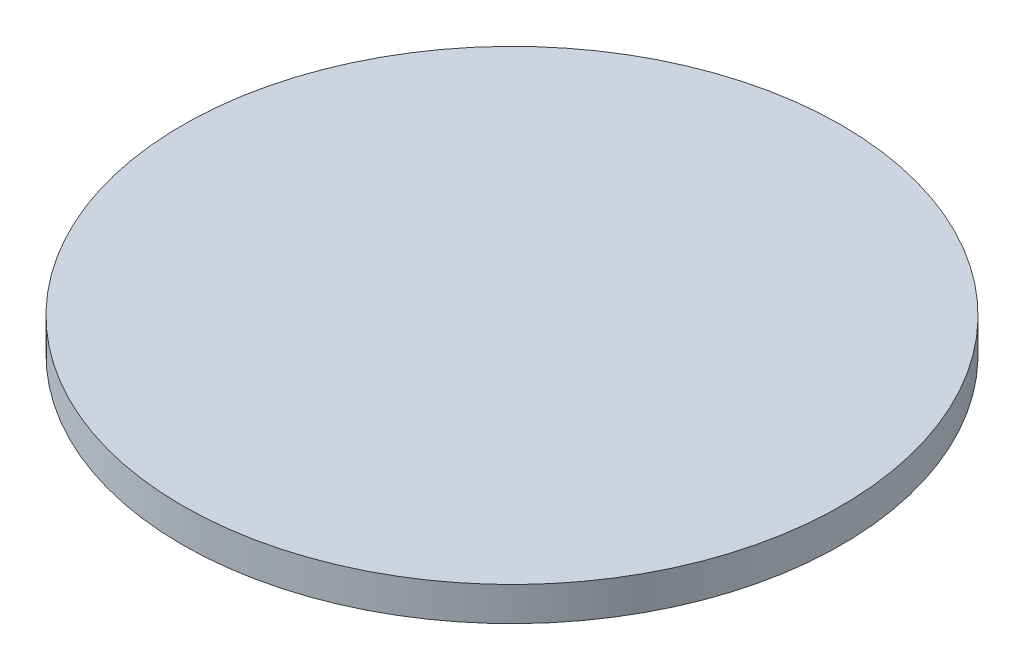
SolidWorks part; units mm, degrees
ref_plane "Front Plane" through (0, 0, 0) normal (0, 0, 1) x (1, 0, 0)
ref_plane "Top Plane" through (0, 0, 0) normal (0, 1, 0) x (1, 0, 0)
ref_plane "Right Plane" through (0, 0, 0) normal (1, 0, 0) x (0, 0, -1)
sketch "Sketch1" plane through (0, 0, 0) normal (0, 1, 0) x (1, 0, 0)
  circle A0 centre (-50.7628, 15.6849) radius 4010
  circle A1 centre (-22.7286, 0) radius 910
  circle A2 centre (16.9802, 0) radius 97.1907
extrude "Boss-Extrude1" add sketch "Sketch1" along normal blind 10 contours A2
